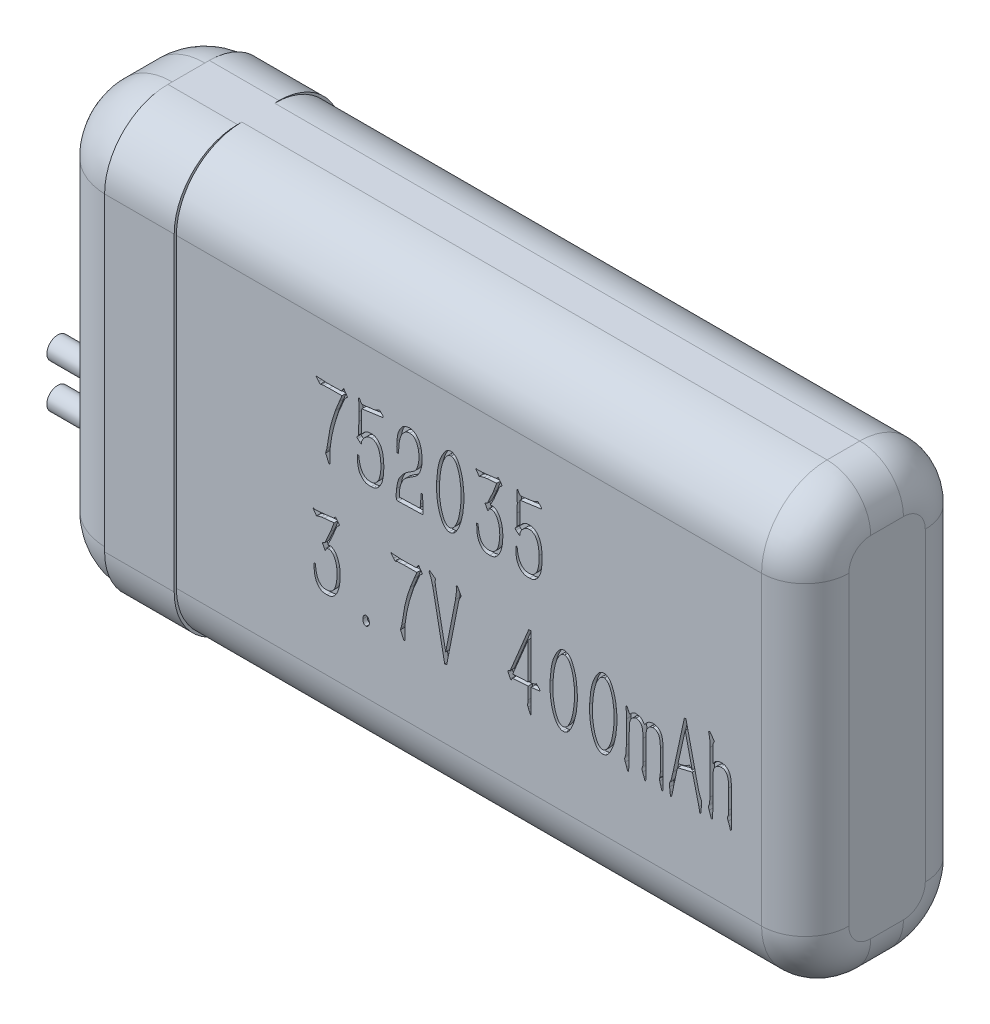
SolidWorks part; units mm, degrees
ref_plane "前视基准面" through (0, 0, 0) normal (0, 0, 1) x (1, 0, 0)
ref_plane "上视基准面" through (0, 0, 0) normal (0, 1, 0) x (1, 0, 0)
ref_plane "右视基准面" through (0, 0, 0) normal (1, 0, 0) x (0, 0, -1)
sketch "草图1" plane through (0, 0, 0) normal (0, 0, 1) x (1, 0, 0)
  line L1 (-7.175, 16.4198) -> (27.825, 16.4198)
  line L2 (-7.175, 16.4198) -> (-7.175, -3.5802)
  line L3 (-7.175, -3.5802) -> (27.825, -3.5802)
  line L4 (27.825, 16.4198) -> (27.825, -3.5802)
  line L5 (-7.175, 16.4198) -> (27.825, -3.5802) construction
  line L6 (-7.175, -3.5802) -> (27.825, 16.4198) construction
  point P4 (10.325, 6.4198)
  dimension "D1" = 35
  dimension "D2" = 20
extrude "凸台-拉伸1" add sketch "草图1" along normal blind 7.5
fillet "圆角1" radius 3 4 edges at (10.325, 16.4198, 0) (10.325, 16.4198, 7.5) (10.325, -3.5802, 0) (10.325, -3.5802, 7.5)
fillet "圆角2" radius 2 8 edges at (27.825, -2.7015, 0.8787) (27.825, -3.5802, 3.75) (27.825, -2.7015, 6.6213) (27.825, 6.4198, 7.5) (27.825, 15.5411, 6.6213) (27.825, 16.4198, 3.75) (27.825, 15.5411, 0.8787) (27.825, 6.4198, 0)
fillet "圆角3" radius 3 8 edges at (-7.175, 15.5411, 6.6213) (-7.175, 6.4198, 7.5) (-7.175, -2.7015, 6.6213) (-7.175, -3.5802, 3.75) (-7.175, -2.7015, 0.8787) (-7.175, 6.4198, 0) (-7.175, 15.5411, 0.8787) (-7.175, 16.4198, 3.75)
sketch "草图2" plane through (0, 0, 7.5) normal (0, 0, 1) x (1, 0, 0)
  line L0 (25.825, -3.5802) -> (-4.175, -3.5802) construction
  line L1 (-4.175, 16.4198) -> (-0.9861, 16.4198)
  line L2 (-4.175, 16.4198) -> (-4.175, -3.5802)
  line L3 (-4.175, -3.5802) -> (-0.9861, -3.5802)
  line L4 (-0.9861, 16.4198) -> (-0.9861, -3.5802)
  line L5 (-4.175, 16.4198) -> (-0.9861, -3.5802) construction
  line L6 (-4.175, -3.5802) -> (-0.9861, 16.4198) construction
  point P4 (-2.5806, 6.4198)
extrude "凸台-拉伸2" add sketch "草图2" against normal blind 7.6 and the other way blind 0.1
fillet "圆角5" radius 2.9 4 edges at (-2.5806, 16.4198, 7.6) (-2.5806, 16.4198, -0.1) (-2.5806, -3.5802, -0.1) (-2.5806, -3.5802, 7.6)
sketch "草图3" plane through (-7.175, 0, 0) normal (-1, 0, 0) x (0, 0, 1)
  circle A1 centre (3.75, 0.502) radius 0.5
extrude "凸台-拉伸3" add sketch "草图3" along normal blind 3
sketch "草图4" plane through (-7.175, 0, 0) normal (-1, 0, 0) x (0, 0, 1)
  circle A0 centre (3.7448, 2.502) radius 0.5
  circle A1 centre (3.75, 0.502) radius 0.5 construction
  dimension "D2" = 1
  dimension "D1" = 2
extrude "凸台-拉伸4" add sketch "草图4" along normal blind 3
sketch "草图5" plane through (0, 0, 7.5) normal (0, 0, 1) x (1, 0, 0)
  text T0 "752035"
  text T1 "3.7V 400mAh"
extrude "切除-拉伸1" cut sketch "草图5" against normal blind 0.2
